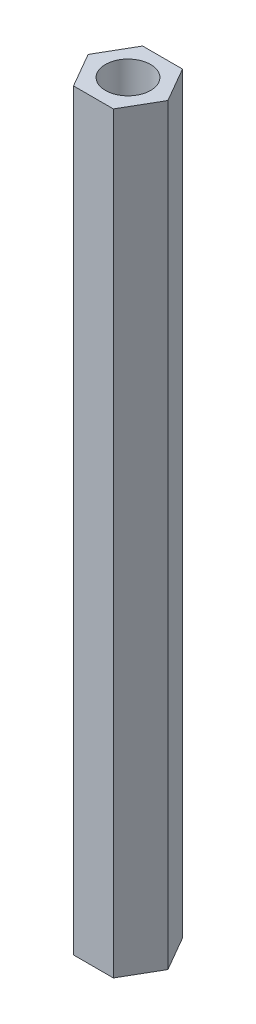
SolidWorks part; units mm, degrees
ref_plane "Alzado" through (0, 0, 0) normal (0, 0, 1) x (1, 0, 0)
ref_plane "Planta" through (0, 0, 0) normal (0, 1, 0) x (1, 0, 0)
ref_plane "Vista lateral" through (0, 0, 0) normal (1, 0, 0) x (0, 0, -1)
sketch "Croquis1" plane through (0, 0, 0) normal (0, 1, 0) x (1, 0, 0)
  line L1 (2.65, 0) -> (1.325, 2.295)
  line L2 (1.325, 2.295) -> (-1.325, 2.295)
  line L3 (-1.325, 2.295) -> (-2.65, 0)
  line L4 (-2.65, 0) -> (-1.325, -2.295)
  line L5 (-1.325, -2.295) -> (1.325, -2.295)
  line L6 (1.325, -2.295) -> (2.65, 0)
  circle A0 centre (0, 0) radius 2.65 construction
extrude "Saliente-Extruir1" add sketch "Croquis1" along normal blind 50
sketch "Croquis2" plane through (0, 50, 0) normal (0, 1, 0) x (1, 0, 0)
  circle A0 centre (0, 0) radius 1.5
  dimension "D1" = 3
extrude "Cortar-Extruir1" cut sketch "Croquis2" against normal blind 50
